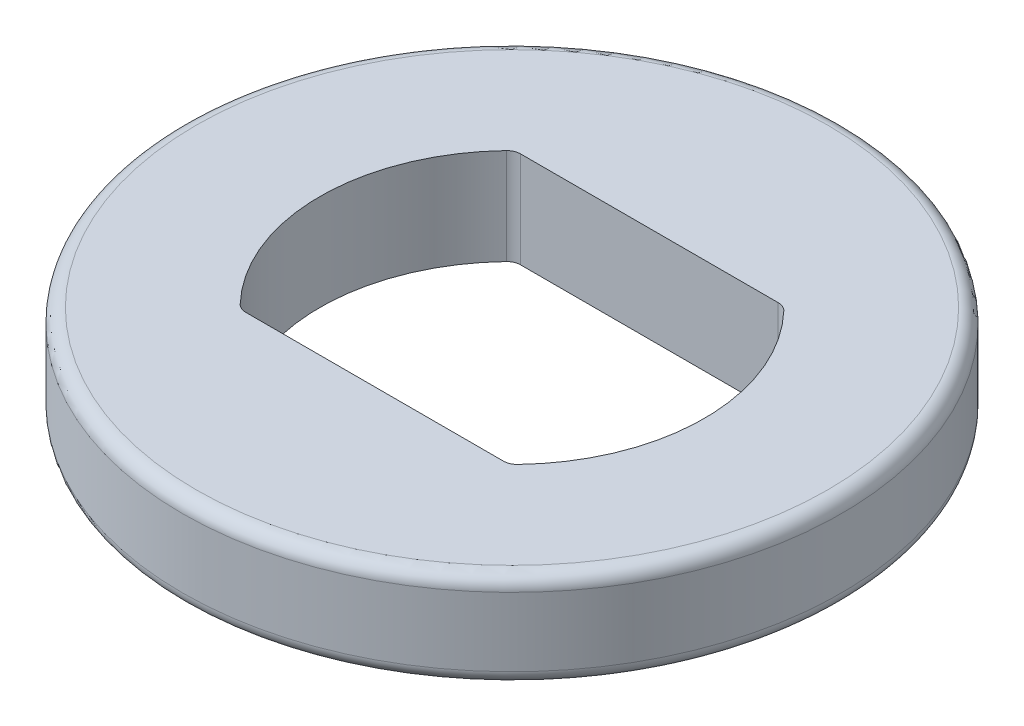
SolidWorks part; units mm, degrees
ref_plane "前视基准面" through (0, 0, 0) normal (0, 0, 1) x (1, 0, 0)
ref_plane "上视基准面" through (0, 0, 0) normal (0, 1, 0) x (1, 0, 0)
ref_plane "右视基准面" through (0, 0, 0) normal (1, 0, 0) x (0, 0, -1)
sketch "草图1" plane through (0, 0, 0) normal (0, 1, 0) x (1, 0, 0)
  circle A0 centre (0, 0) radius 12
  dimension "D1" = 24
extrude "凸台-拉伸1" add sketch "草图1" along normal blind 3.5
sketch "草图2" plane through (0, 0, 0) normal (0, -1, 0) x (1, 0, 0)
  line L1 (4.899, -5) -> (-4.899, -5)
  line L3 (4.899, 5) -> (-4.899, 5)
  arc A0 (-4.899, 5) -> (-4.899, -5) centre (0, 0) ccw
  arc A1 (4.899, -5) -> (4.899, 5) centre (0, 0) ccw
  dimension "D1" = 14
  dimension "D2" = 10
  dimension "D3" = 5
extrude "切除-拉伸1" cut sketch "草图2" against normal through all
fillet "圆角1" radius 0.5 6 edges at (0, 3.5, 12) (0, 0, 12) (-4.899, 1.75, -5) (4.899, 1.75, -5) (4.899, 1.75, 5) (-4.899, 1.75, 5)
